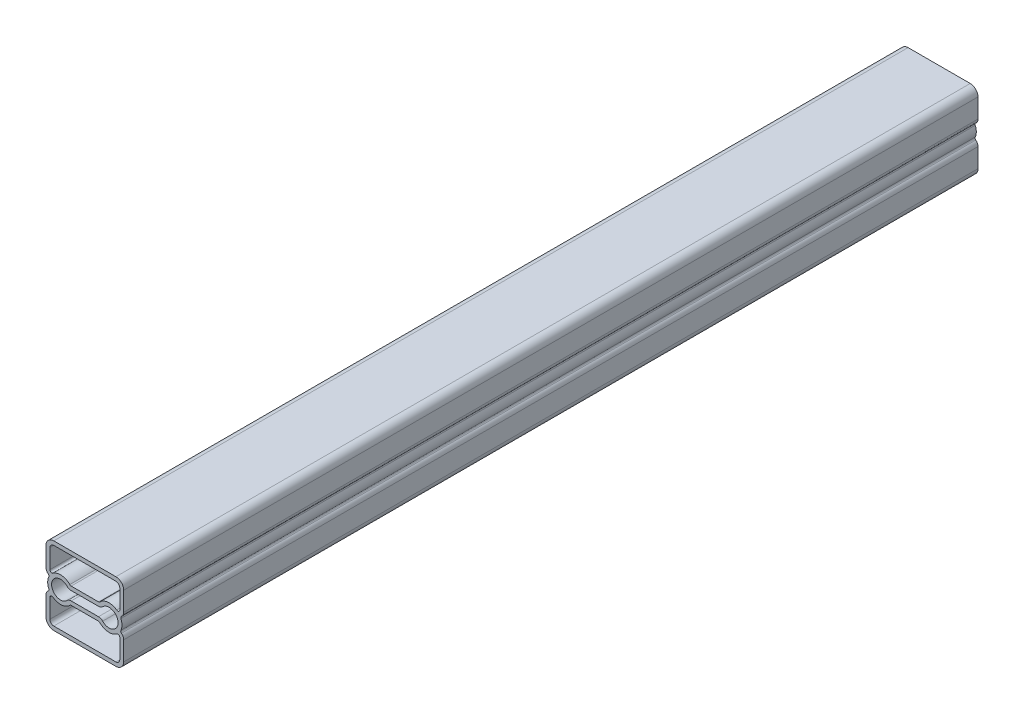
SolidWorks part; units mm, degrees
ref_plane "Front Plane" through (0, 0, 0) normal (0, 0, 1) x (1, 0, 0)
ref_plane "Top Plane" through (0, 0, 0) normal (0, 1, 0) x (1, 0, 0)
ref_plane "Right Plane" through (0, 0, 0) normal (1, 0, 0) x (0, 0, -1)
sketch "Sketch1" plane through (0, 0, 0) normal (0, 0, 1) x (1, 0, 0)
  line L0 (4.4671, -1.4668) -> (-4.4671, -1.4668)
  line L1 (-4.4671, 1.4668) -> (4.4671, 1.4668)
  line L2 (12.7, 3.9048) -> (12.7, 10.16)
  line L3 (10.16, 12.7) -> (-10.16, 12.7)
  line L4 (-12.7, 10.16) -> (-12.7, 3.9048)
  line L5 (-12.7, -3.9048) -> (-12.7, -10.16)
  line L6 (-10.16, -12.7) -> (10.16, -12.7)
  line L7 (12.7, -10.16) -> (12.7, -3.9048)
  line L8 (11.43, 10.16) -> (11.43, 3.9048)
  line L9 (4.4671, 2.7368) -> (-4.4671, 2.7368)
  line L10 (-11.43, 3.9048) -> (-11.43, 10.16)
  line L11 (-10.16, 11.43) -> (10.16, 11.43)
  line L12 (11.43, -3.9048) -> (11.43, -10.16)
  line L13 (10.16, -11.43) -> (-10.16, -11.43)
  line L14 (-11.43, -10.16) -> (-11.43, -3.9048)
  line L15 (-4.4671, -2.7368) -> (4.4671, -2.7368)
  arc A0 (5.8334, -2.0443) -> (4.4671, -1.4668) centre (4.4671, -3.3718) ccw
  arc A1 (-4.4671, -1.4668) -> (-5.8334, -2.0443) centre (-4.4671, -3.3718) ccw
  arc A2 (-5.8334, -2.0443) -> (-5.8334, 2.0443) centre (-7.9375, 0) cw
  arc A3 (-5.8334, 2.0443) -> (-4.4671, 1.4668) centre (-4.4671, 3.3718) ccw
  arc A4 (4.4671, 1.4668) -> (5.8334, 2.0443) centre (4.4671, 3.3718) ccw
  arc A5 (5.8334, 2.0443) -> (5.8334, -2.0443) centre (7.9375, 0) cw
  arc A6 (11.9832, 2.4158) -> (12.7, 3.9048) centre (10.795, 3.9048) ccw
  arc A7 (12.7, 10.16) -> (10.16, 12.7) centre (10.16, 10.16) ccw
  arc A8 (-10.16, 12.7) -> (-12.7, 10.16) centre (-10.16, 10.16) ccw
  arc A9 (-12.7, 3.9048) -> (-11.9832, 2.4158) centre (-10.795, 3.9048) ccw
  arc A10 (-11.9832, 2.4158) -> (-11.7963, 1.6675) centre (-12.3792, 1.9194) cw
  arc A11 (-11.7963, 1.6675) -> (-11.7963, -1.6675) centre (-7.9375, 0) ccw
  arc A12 (-11.7963, -1.6675) -> (-11.9832, -2.4158) centre (-12.3792, -1.9194) cw
  arc A13 (-11.9832, -2.4158) -> (-12.7, -3.9048) centre (-10.795, -3.9048) ccw
  arc A14 (-12.7, -10.16) -> (-10.16, -12.7) centre (-10.16, -10.16) ccw
  arc A15 (10.16, -12.7) -> (12.7, -10.16) centre (10.16, -10.16) ccw
  arc A16 (12.7, -3.9048) -> (11.9832, -2.4158) centre (10.795, -3.9048) ccw
  arc A17 (11.9832, -2.4158) -> (11.7963, -1.6675) centre (12.3792, -1.9194) cw
  arc A18 (11.7963, -1.6675) -> (11.7963, 1.6675) centre (7.9375, 0) ccw
  arc A19 (11.7963, 1.6675) -> (11.9832, 2.4158) centre (12.3792, 1.9194) cw
  arc A20 (10.16, 11.43) -> (11.43, 10.16) centre (10.16, 10.16) cw
  arc A21 (11.43, 3.9048) -> (10.42, 3.3924) centre (10.795, 3.9048) cw
  arc A22 (10.42, 3.3924) -> (4.9225, 2.9293) centre (7.9375, 0) ccw
  arc A23 (4.9225, 2.9293) -> (4.4671, 2.7368) centre (4.4671, 3.3718) cw
  arc A24 (-4.4671, 2.7368) -> (-4.9225, 2.9293) centre (-4.4671, 3.3718) cw
  arc A25 (-4.9225, 2.9293) -> (-10.42, 3.3924) centre (-7.9375, 0) ccw
  arc A26 (-10.42, 3.3924) -> (-11.43, 3.9048) centre (-10.795, 3.9048) cw
  arc A27 (-11.43, 10.16) -> (-10.16, 11.43) centre (-10.16, 10.16) cw
  arc A28 (4.4671, -2.7368) -> (4.9225, -2.9293) centre (4.4671, -3.3718) cw
  arc A29 (4.9225, -2.9293) -> (10.42, -3.3924) centre (7.9375, 0) ccw
  arc A30 (10.42, -3.3924) -> (11.43, -3.9048) centre (10.795, -3.9048) cw
  arc A31 (11.43, -10.16) -> (10.16, -11.43) centre (10.16, -10.16) cw
  arc A32 (-10.16, -11.43) -> (-11.43, -10.16) centre (-10.16, -10.16) cw
  arc A33 (-11.43, -3.9048) -> (-10.42, -3.3924) centre (-10.795, -3.9048) cw
  arc A34 (-10.42, -3.3924) -> (-4.9225, -2.9293) centre (-7.9375, 0) ccw
  arc A35 (-4.9225, -2.9293) -> (-4.4671, -2.7368) centre (-4.4671, -3.3718) cw
extrude "Boss-Extrude1" add sketch "Sketch1" against normal blind 279.4
